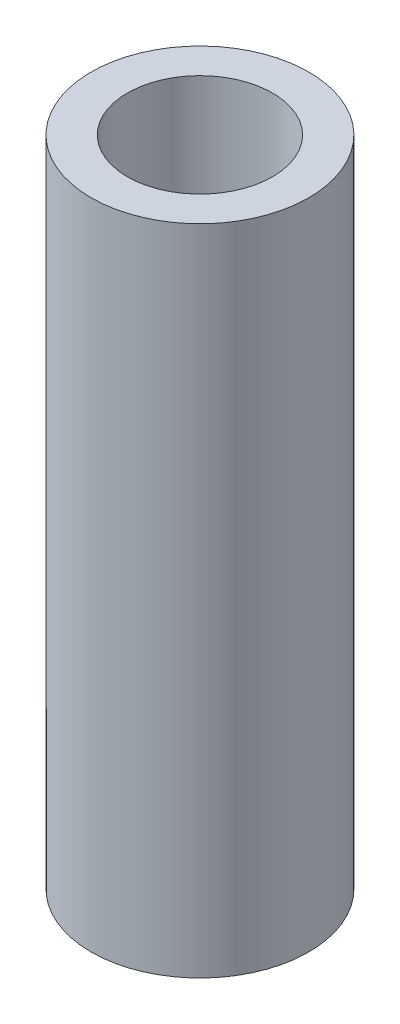
SolidWorks part; units mm, degrees
ref_plane "Спереди" through (0, 0, 0) normal (0, 0, 1) x (1, 0, 0)
ref_plane "Сверху" through (0, 0, 0) normal (0, 1, 0) x (1, 0, 0)
ref_plane "Справа" through (0, 0, 0) normal (1, 0, 0) x (0, 0, -1)
sketch "Эскиз1" plane through (0, 0, 0) normal (0, 1, 0) x (1, 0, 0)
  circle A0 centre (0, 0) radius 2
  circle A1 centre (0, 0) radius 3
  dimension "D1" = 4
  dimension "D2" = 6
extrude "Бобышка-Вытянуть1" add sketch "Эскиз1" along normal blind 18
